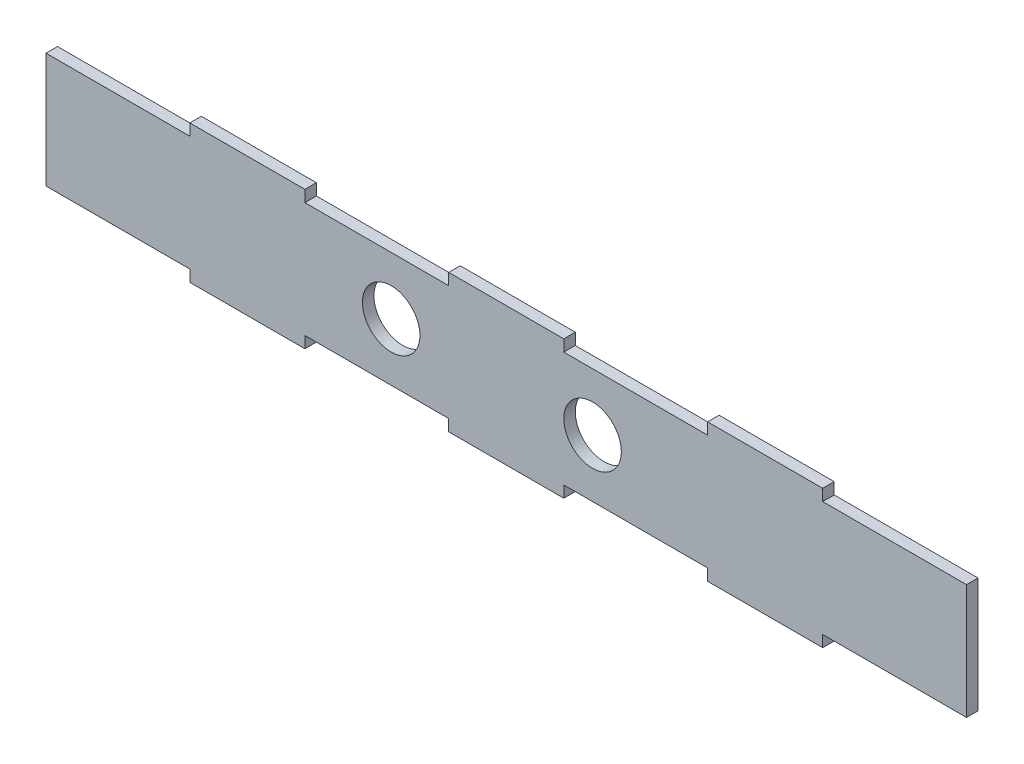
SolidWorks part; units mm, degrees
ref_plane "Спереди" through (0, 0, 0) normal (0, 0, 1) x (1, 0, 0)
ref_plane "Сверху" through (0, 0, 0) normal (0, 1, 0) x (1, 0, 0)
ref_plane "Справа" through (0, 0, 0) normal (1, 0, 0) x (0, 0, -1)
sketch "Эскиз1" plane through (0, 0, 0) normal (0, 0, 1) x (1, 0, 0)
  line L1 (0, 0) -> (160, 0)
  line L2 (0, 0) -> (0, 24)
  line L3 (0, 24) -> (160, 24)
  line L4 (160, 0) -> (160, 24)
  line L5 (0, 24) -> (25, 24)
  line L6 (0, 24) -> (0, 22)
  line L7 (0, 22) -> (25, 22)
  line L8 (25, 24) -> (25, 22)
  line L9 (45, 24) -> (70, 24)
  line L10 (45, 24) -> (45, 22)
  line L11 (45, 22) -> (70, 22)
  line L12 (70, 24) -> (70, 22)
  line L13 (90, 24) -> (115, 24)
  line L14 (90, 24) -> (90, 22)
  line L15 (90, 22) -> (115, 22)
  line L16 (115, 24) -> (115, 22)
  line L17 (0, 0) -> (25, 0)
  line L18 (0, 0) -> (0, 2)
  line L19 (0, 2) -> (25, 2)
  line L20 (25, 0) -> (25, 2)
  line L21 (45, 0) -> (70, 0)
  line L22 (45, 0) -> (45, 2)
  line L23 (45, 2) -> (70, 2)
  line L24 (70, 0) -> (70, 2)
  line L25 (90, 0) -> (115, 0)
  line L26 (90, 0) -> (90, 2)
  line L27 (90, 2) -> (115, 2)
  line L28 (115, 0) -> (115, 2)
  line L29 (160, 24) -> (135, 24)
  line L30 (160, 24) -> (160, 22)
  line L31 (160, 22) -> (135, 22)
  line L32 (135, 24) -> (135, 22)
  line L33 (160, 0) -> (135, 0)
  line L34 (160, 0) -> (160, 2)
  line L35 (160, 2) -> (135, 2)
  line L36 (135, 0) -> (135, 2)
  circle A0 centre (95, 12) radius 5
  circle A1 centre (60, 12) radius 5
  dimension "D25" = 10
  dimension "D28" = 10
  dimension "D1" = 24
  dimension "D2" = 160
  dimension "D3" = 2
  dimension "D4" = 2
  dimension "D5" = 2
  dimension "D6" = 2
  dimension "D7" = 2
  dimension "D8" = 2
  dimension "D9" = 25
  dimension "D10" = 25
  dimension "D11" = 25
  dimension "D12" = 25
  dimension "D13" = 25
  dimension "D14" = 25
  dimension "D15" = 20
  dimension "D16" = 20
  dimension "D17" = 20
  dimension "D18" = 20
  dimension "D19" = 20
  dimension "D20" = 20
  dimension "D21" = 2
  dimension "D22" = 2
  dimension "D26" = 12
  dimension "D27" = 65
  dimension "D29" = 12
  dimension "100" = 100
extrude "Бобышка-Вытянуть1" add sketch "Эскиз1" along normal blind 2 contours L1 L36 L35 L4 L31 L32 L3 L16 L15 L14 L12 L11 L10 L8 L7 L2 L19 L20 L22 L23 L24 L26 L27 L28
